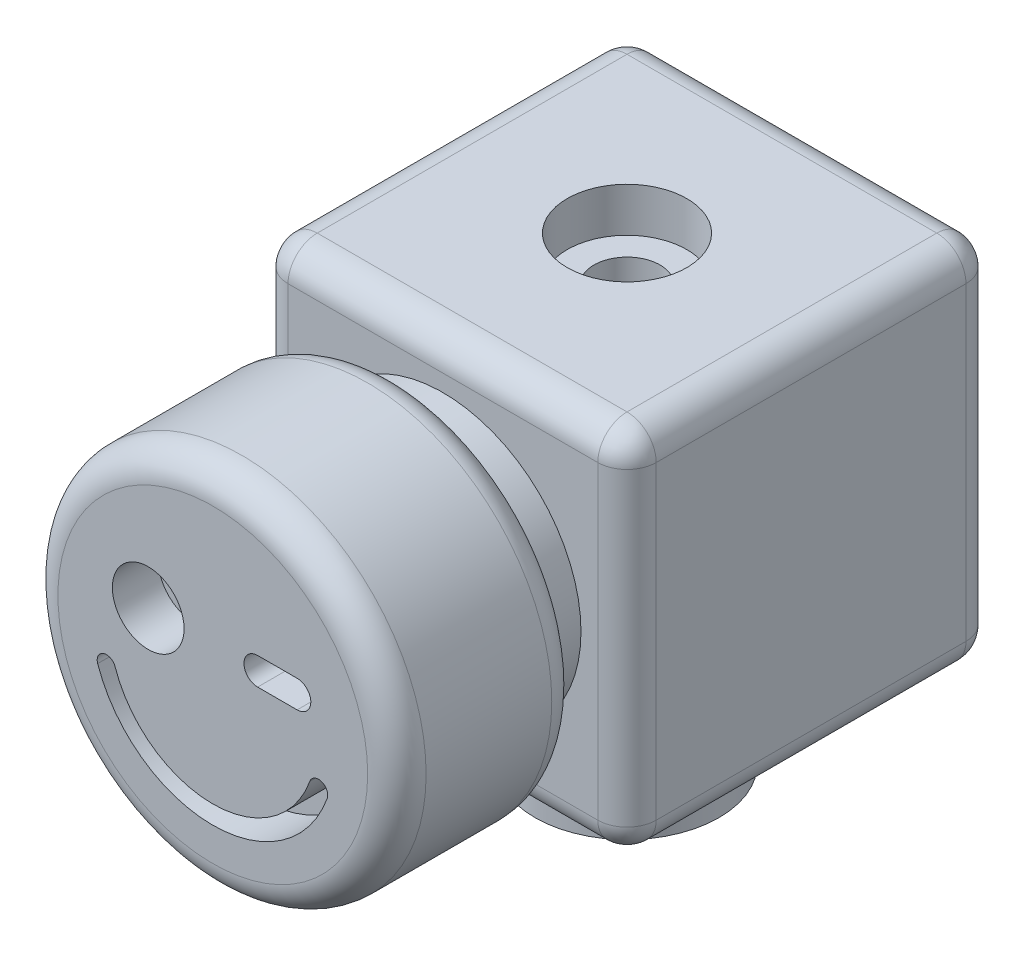
SolidWorks part; units mm, degrees
ref_plane "Front Plane" through (0, 0, 0) normal (0, 0, 1) x (1, 0, 0)
ref_plane "Top Plane" through (0, 0, 0) normal (0, 1, 0) x (1, 0, 0)
ref_plane "Right Plane" through (0, 0, 0) normal (1, 0, 0) x (0, 0, -1)
sketch "Sketch1" plane through (0, 0, 0) normal (0, 1, 0) x (1, 0, 0)
  circle A0 centre (0, 0) radius 5
  point P0 (0, 0)
  dimension "D1" = 10
extrude "Boss-Extrude1" add sketch "Sketch1" along normal blind 5
sketch "Sketch2" plane through (0, 5, 0) normal (0, 1, 0) x (1, 0, 0)
  line L1 (-10, -10) -> (10, -10)
  line L2 (-10, -10) -> (-10, 10)
  line L3 (-10, 10) -> (10, 10)
  line L4 (10, -10) -> (10, 10)
  line L5 (-10, -10) -> (10, 10) construction
  line L6 (-10, 10) -> (10, -10) construction
  point P0 (0, 0)
  dimension "D1" = 20
  dimension "D2" = 20
extrude "Boss-Extrude2" add sketch "Sketch2" along normal blind 20
sketch "Sketch3" plane through (0, 0, 10) normal (0, 0, 1) x (1, 0, 0)
  circle A2 centre (0, 15) radius 7.5
  dimension "D1" = 15
extrude "Boss-Extrude4" add sketch "Sketch3" along normal blind 2.5
sketch "Sketch4" plane through (0, 0, 12.5) normal (0, 0, 1) x (1, 0, 0)
  circle A0 centre (0, 15) radius 10
  dimension "D1" = 20
extrude "Boss-Extrude5" add sketch "Sketch4" along normal blind 10
hole_wizard "CBORE for M3 Hex Socket Thin Head Cap Screw1" positions "Sketch5" profile "Sketch6" counterbore size "M3" standard "DIN" end condition through all
sketch "Sketch5" plane through (0, 25, 0) normal (0, 1, 0) x (1, 0, 0)
  point P0 (0, 0)
sketch "Sketch6" plane through (0, 25, 0) normal (1, 0, 0) x (0, 0, 1)
  line L0 (0, 0) -> (0, 25)
  line L1 (0, 25) -> (1.8, 25)
  line L3 (1.8, 25) -> (1.8, 2.4)
  line L4 (1.8, 2.4) -> (3.25, 2.4)
  line L5 (3.25, 2.4) -> (3.25, 0)
  line L7 (3.25, 0) -> (0, 0)
  line L11 (0, -6.35) -> (0, 107.95) construction
  dimension "Thru Hole Dia." = 3.6
  dimension "Thru Hole Depth" = 25
  dimension "C'Bore Dia." = 6.5
  dimension "C'Bore Depth" = 2.4
fillet "Fillet1" radius 1.5875 14 edges at (0, 5, 10) (10, 15, 22.5) (10, 15, 10) (10, 25, 0) (10, 5, 0) (-10, 25, 0) (-10, 15, 10) (-10, 5, 0) (10, 15, -10) (0, 25, -10) (-10, 15, -10) (0, 5, -10) (10, 15, 12.5) (0, 25, 10)
sketch "Sketch7" plane through (0, 0, 22.5) normal (0, 0, 1) x (1, 0, 0)
  line L0 (0, 15) -> (0, 16.8545) construction
  line L1 (-3.5084, 16.8545) -> (3.5084, 16.8545) construction
  line L2 (2.4352, 16.8545) -> (4.5815, 16.8545) construction
  line L3 (2.4352, 17.5975) -> (4.5815, 17.5975)
  line L4 (2.4352, 16.1116) -> (4.5815, 16.1116)
  arc A0 (-6.2532, 12.8715) -> (6.2132, 12.7574) centre (0, 15) ccw
  arc A1 (-5.3065, 13.1937) -> (5.2726, 13.0969) centre (0, 15) ccw
  arc A2 (6.2132, 12.7574) -> (5.2726, 13.0969) centre (5.7429, 12.9272) ccw
  arc A3 (-5.3065, 13.1937) -> (-6.2532, 12.8715) centre (-5.7799, 13.0326) ccw
  circle A4 centre (-3.5084, 16.8545) radius 1.9483
  arc A5 (2.4352, 17.5975) -> (2.4352, 16.1116) centre (2.4352, 16.8545) ccw
  arc A6 (4.5815, 16.1116) -> (4.5815, 17.5975) centre (4.5815, 16.8545) ccw
  point P14 (0, 16.8545)
  point P17 (3.5084, 16.8545)
  point P22 (3.6116, 17.4737)
  point P23 (0, 16.7307)
  point P24 (4.953, 16.8752)
  point P25 (4.4371, 16.8752)
  point P26 (3.5084, 16.8545)
  point P27 (3.075, 16.8133)
  point P28 (-3.5084, 16.8133)
  point P29 (-3.5084, 16.8133)
  point P30 (4.5815, 16.8545)
extrude "Cut-Extrude2" cut sketch "Sketch7" against normal blind 2.5
